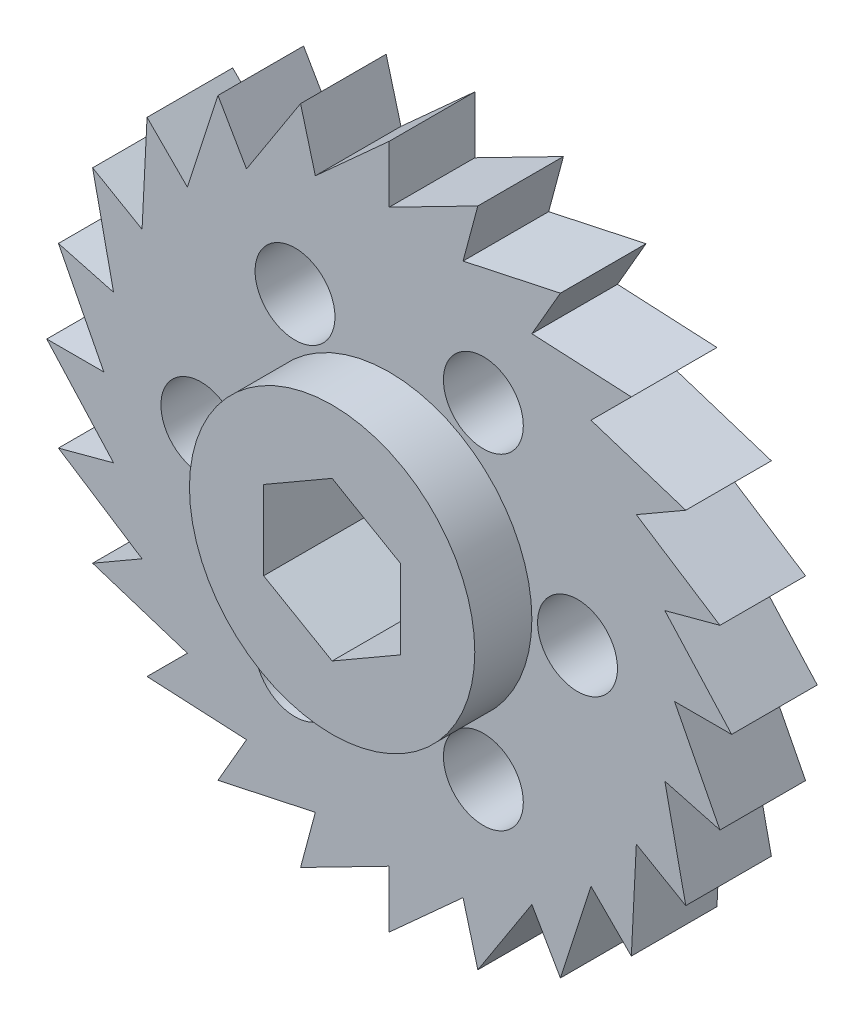
SolidWorks part; units mm, degrees
ref_plane "前视基准面" through (0, 0, 0) normal (0, 0, 1) x (1, 0, 0)
ref_plane "上视基准面" through (0, 0, 0) normal (0, 1, 0) x (1, 0, 0)
ref_plane "右视基准面" through (0, 0, 0) normal (1, 0, 0) x (0, 0, -1)
sketch "草图1" plane through (0, 0, 0) normal (0, 0, 1) x (1, 0, 0)
  line L0 (50, 0) -> (60, 0)
  line L1 (60, 0) -> (48.2963, 12.9409)
  line L2 (48.2963, 12.9409) -> (57.9556, 15.5291)
  line L3 (57.9556, 15.5291) -> (43.3013, 25)
  line L4 (43.3013, 25) -> (51.9615, 30)
  line L5 (51.9615, 30) -> (35.3553, 35.3553)
  line L6 (35.3553, 35.3553) -> (42.4264, 42.4264)
  line L7 (42.4264, 42.4264) -> (25, 43.3013)
  line L8 (25, 43.3013) -> (30, 51.9615)
  line L9 (30, 51.9615) -> (12.9409, 48.2963)
  line L10 (12.9409, 48.2963) -> (15.5291, 57.9556)
  line L11 (15.5291, 57.9556) -> (0, 50)
  line L12 (0, 50) -> (0, 60)
  line L13 (0, 60) -> (-12.9409, 48.2963)
  line L14 (-12.9409, 48.2963) -> (-15.5291, 57.9556)
  line L15 (-15.5291, 57.9556) -> (-25, 43.3013)
  line L16 (-25, 43.3013) -> (-30, 51.9615)
  line L17 (-30, 51.9615) -> (-35.3553, 35.3553)
  line L18 (-35.3553, 35.3553) -> (-42.4264, 42.4264)
  line L19 (-42.4264, 42.4264) -> (-43.3013, 25)
  line L20 (-43.3013, 25) -> (-51.9615, 30)
  line L21 (-51.9615, 30) -> (-48.2963, 12.9409)
  line L22 (-48.2963, 12.9409) -> (-57.9556, 15.5291)
  line L23 (-57.9556, 15.5291) -> (-50, 0)
  line L24 (-50, 0) -> (-60, 0)
  line L25 (-60, 0) -> (-48.2963, -12.9409)
  line L26 (-48.2963, -12.9409) -> (-57.9556, -15.5291)
  line L27 (-57.9556, -15.5291) -> (-43.3013, -25)
  line L28 (-43.3013, -25) -> (-51.9615, -30)
  line L29 (-51.9615, -30) -> (-35.3553, -35.3553)
  line L30 (-35.3553, -35.3553) -> (-42.4264, -42.4264)
  line L31 (-42.4264, -42.4264) -> (-25, -43.3013)
  line L32 (-25, -43.3013) -> (-30, -51.9615)
  line L33 (-30, -51.9615) -> (-12.9409, -48.2963)
  line L34 (-12.9409, -48.2963) -> (-15.5291, -57.9556)
  line L35 (-15.5291, -57.9556) -> (0, -50)
  line L36 (0, -50) -> (0, -60)
  line L37 (0, -60) -> (12.9409, -48.2963)
  line L38 (12.9409, -48.2963) -> (15.5291, -57.9556)
  line L39 (15.5291, -57.9556) -> (25, -43.3013)
  line L40 (25, -43.3013) -> (30, -51.9615)
  line L41 (30, -51.9615) -> (35.3553, -35.3553)
  line L42 (35.3553, -35.3553) -> (42.4264, -42.4264)
  line L43 (42.4264, -42.4264) -> (43.3013, -25)
  line L44 (43.3013, -25) -> (51.9615, -30)
  line L45 (51.9615, -30) -> (48.2963, -12.9409)
  line L46 (48.2963, -12.9409) -> (57.9556, -15.5291)
  line L47 (57.9556, -15.5291) -> (50, 0)
extrude "凸台-拉伸1" add sketch "草图1" along normal blind 15
ref_plane "基准面1" through (0, 0, 15) normal (0, 0, 1) x (1, 0, 0)
sketch "草图2" plane through (0, 0, 15) normal (0, 0, 1) x (1, 0, 0)
  circle A0 centre (0, 0) radius 25
extrude "凸台-拉伸2" add sketch "草图2" along normal blind 10
ref_plane "基准面2" through (0, 0, 25) normal (0, 0, 1) x (1, 0, 0)
sketch "草图3" plane through (0, 0, 25) normal (0, 0, 1) x (1, 0, 0)
  line L0 (12, 6.9282) -> (0, 13.8564)
  line L1 (0, 13.8564) -> (-12, 6.9282)
  line L2 (-12, 6.9282) -> (-12, -6.9282)
  line L3 (-12, -6.9282) -> (0, -13.8564)
  line L4 (0, -13.8564) -> (12, -6.9282)
  line L5 (12, -6.9282) -> (12, 6.9282)
extrude "切除-拉伸1" cut sketch "草图3" against normal mid plane 242
sketch "草图4" plane through (0, 0, 15) normal (0, 0, 1) x (1, 0, 0)
  circle A0 centre (33, 0) radius 7
  circle A1 centre (16.5, 28.5788) radius 7
  circle A2 centre (-16.5, 28.5788) radius 7
  circle A3 centre (-33, 0) radius 7
  circle A4 centre (-16.5, -28.5788) radius 7
  circle A5 centre (16.5, -28.5788) radius 7
extrude "切除-拉伸2" cut sketch "草图4" against normal mid plane 242
